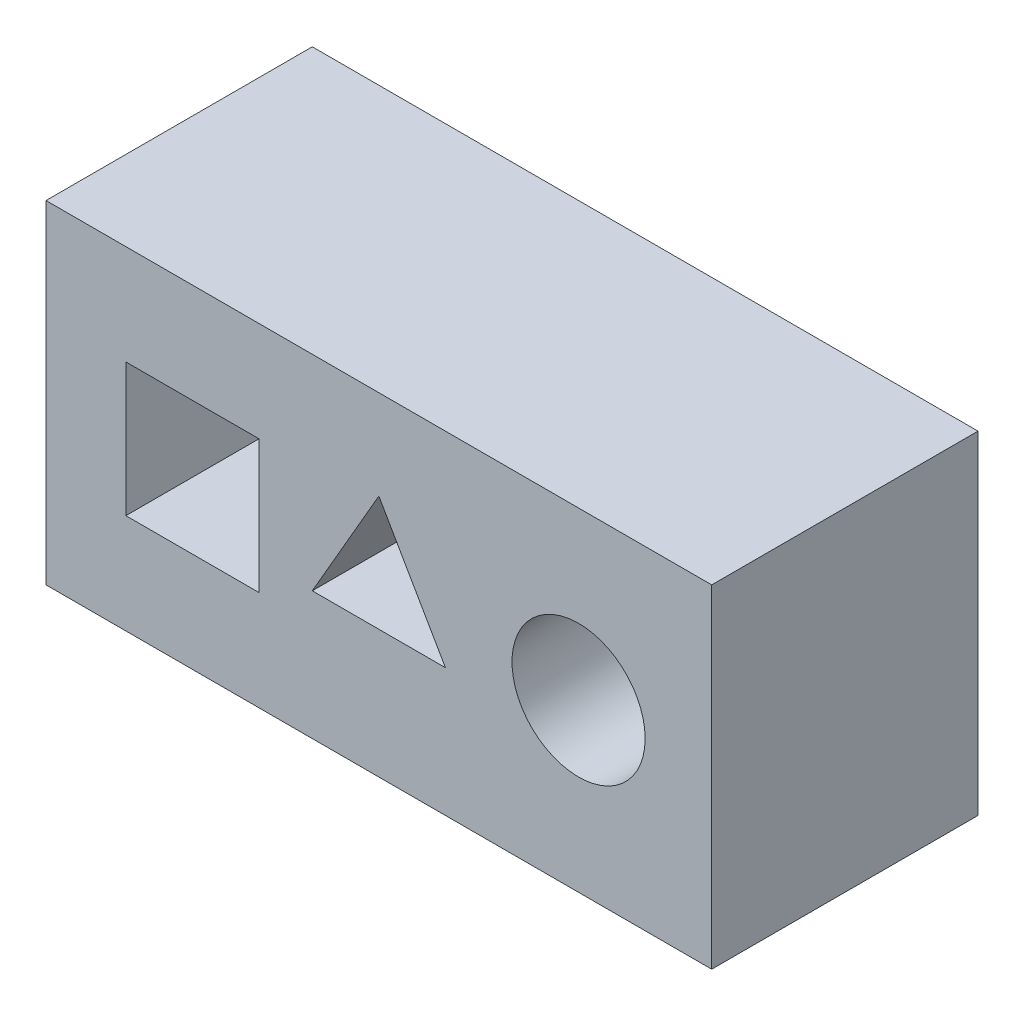
SolidWorks part; units mm, degrees
ref_plane "Front Plane" through (0, 0, 0) normal (0, 0, 1) x (1, 0, 0)
ref_plane "Top Plane" through (0, 0, 0) normal (0, 1, 0) x (1, 0, 0)
ref_plane "Right Plane" through (0, 0, 0) normal (1, 0, 0) x (0, 0, -1)
sketch "Sketch1" plane through (0, 0, 0) normal (0, 0, 1) x (1, 0, 0)
  line L1 (125, -62.5) -> (-125, -62.5)
  line L2 (125, -62.5) -> (125, 62.5)
  line L3 (125, 62.5) -> (-125, 62.5)
  line L4 (-125, -62.5) -> (-125, 62.5)
  line L5 (125, -62.5) -> (-125, 62.5) construction
  line L6 (125, 62.5) -> (-125, -62.5) construction
  line L7 (115, -57.5) -> (-115, -57.5)
  line L8 (115, -57.5) -> (115, 57.5)
  line L9 (115, 57.5) -> (-115, 57.5)
  line L10 (-115, -57.5) -> (-115, 57.5)
  line L11 (115, -57.5) -> (-115, 57.5) construction
  line L12 (115, 57.5) -> (-115, -57.5) construction
  point P0 (0, 0)
  point P6 (0, 0)
  dimension "D1" = 250
  dimension "D2" = 125
  dimension "D3" = 230
extrude "Boss-Extrude1" add sketch "Sketch1" along normal blind 100
sketch "Sketch2" plane through (0, 0, 0) normal (0, 0, -1) x (-1, 0, 0)
  line L1 (125, 62.5) -> (-125, 62.5)
  line L2 (125, 62.5) -> (125, -62.5)
  line L3 (125, -62.5) -> (-125, -62.5)
  line L4 (-125, 62.5) -> (-125, -62.5)
sketch "Sketch3" plane through (0, 0, 100) normal (0, 0, 1) x (1, 0, 0)
  line L0 (-125, 0) -> (125, 0) construction
  line L1 (-125, 62.5) -> (125, 62.5)
  line L2 (-125, 62.5) -> (-125, -62.5)
  line L3 (-125, -62.5) -> (125, -62.5)
  line L4 (125, 62.5) -> (125, -62.5)
  line L5 (0, 62.5) -> (0, -62.5) construction
  line L6 (-25, -14.4338) -> (0, 28.8675)
  line L7 (-95, 25) -> (-45, 25)
  line L8 (-95, 25) -> (-95, -25)
  line L9 (-95, -25) -> (-45, -25)
  line L10 (-45, 25) -> (-45, -25)
  line L11 (-95, 25) -> (-45, -25) construction
  line L12 (-95, -25) -> (-45, 25) construction
  line L14 (-1.3522, 0) -> (0, -1.3522)
  line L18 (0, 28.8675) -> (25, -14.4338)
  line L19 (25, -14.4338) -> (-25, -14.4338)
  line L20 (-25, -14.4338) -> (12.5, 7.2169) construction
  line L21 (25, -14.4338) -> (-12.5, 7.2169) construction
  line L22 (0, 28.8675) -> (0, 0) construction
  circle A0 centre (75, 0) radius 25
  point P10 (-70, 0)
  point P20 (0, 0)
  point P27 (7.7505, -5.3087)
  point P28 (0, 0)
  line M21 (-125, 62.5) -> (-125, -62.5)
  line M22 (-125, -62.5) -> (125, -62.5)
  line M23 (125, -62.5) -> (125, 62.5)
  line M24 (125, 62.5) -> (-125, 62.5)
  line M25 (115, -57.5) -> (-115, -57.5)
  line M26 (-115, -57.5) -> (-115, 57.5)
  line M27 (-115, 57.5) -> (115, 57.5)
  line M28 (115, 57.5) -> (115, -57.5)
  dimension "D2" = 50
  dimension "cylinder" = 50
  dimension "D1" = 30
  dimension "square2" = 50
  dimension "square" = 50
  dimension "triangle3" = 50
  dimension "triangle2" = 50
  dimension "triangle" = 50
extrude "Boss-Extrude4" add sketch "Sketch3" against normal up to surface (100 mm away) contours A0 L7 L10 L9 L8 L18 L19 L6 M25 M28 M27 M26 | M24 M21 M22 M23 M28 M25 M26 M27 up to face at (0, 0, 0)
